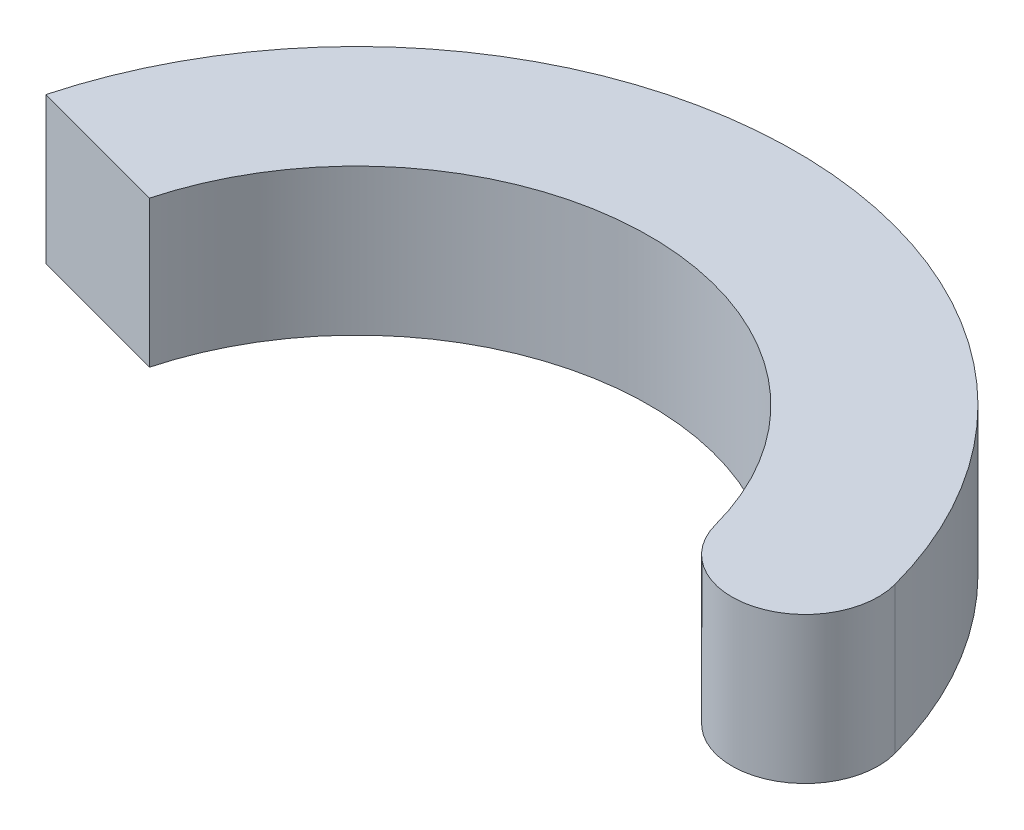
SolidWorks part; units mm, degrees
ref_plane "Front Plane" through (0, 0, 0) normal (0, 0, 1) x (1, 0, 0)
ref_plane "Top Plane" through (0, 0, 0) normal (0, 1, 0) x (1, 0, 0)
ref_plane "Right Plane" through (0, 0, 0) normal (1, 0, 0) x (0, 0, -1)
sketch "Sketch2" plane through (0, 0, 0) normal (0, 1, 0) x (1, 0, 0)
  line L0 (-38.637, 10.3528) -> (-57.9555, 15.5291) construction
  line L1 (0, -66) -> (0, 66) construction
  circle A0 centre (0, 0) radius 40
  circle A1 centre (0, 0) radius 60
  arc A2 (-57.9555, 15.5291) -> (-38.637, 10.3528) centre (-48.2963, 12.941) ccw
  arc A3 (57.9555, 15.5291) -> (38.637, 10.3528) centre (48.2963, 12.941) cw
  dimension "D1" = 20
  dimension "D2" = 120
  dimension "D3" = 75
extrude "Boss-Extrude1" add sketch "Sketch2" along normal blind 20
